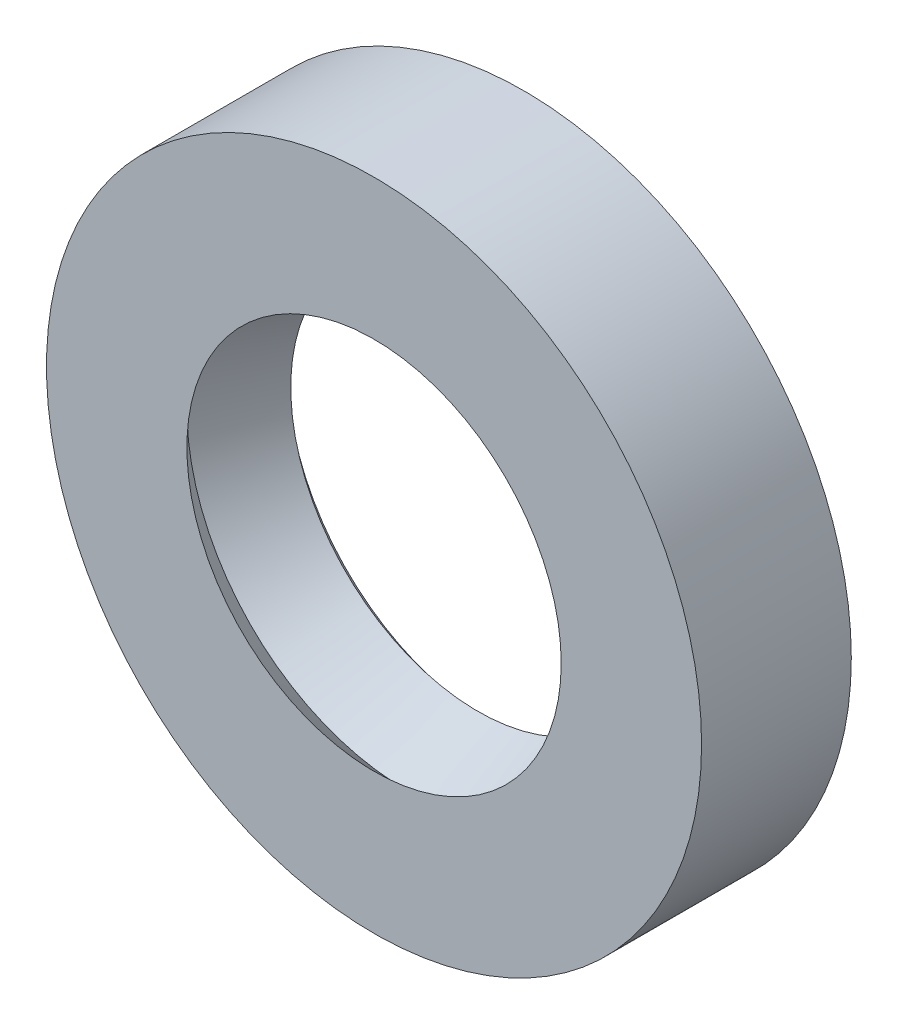
SolidWorks part; units mm, degrees
material "Silicon Rubber"
ref_plane "Front Plane" through (0, 0, 0) normal (0, 0, 1) x (1, 0, 0)
ref_plane "Top Plane" through (0, 0, 0) normal (0, 1, 0) x (1, 0, 0)
ref_plane "Right Plane" through (0, 0, 0) normal (1, 0, 0) x (0, 0, -1)
sketch "Sketch1" plane through (0, 0, 0) normal (1, 0, 0) x (0, 0, -1)
  line L0 (0, 17.5) -> (0, -17.5) construction
  line L1 (-20.6631, 0) -> (18.0254, 0) construction
  line L2 (0, 17.5) -> (-8, 17.5)
  line L3 (-8, 17.5) -> (-8, 0)
  line L4 (0, 15.75) -> (-6.25, 15.75)
  line L5 (-6.25, 15.75) -> (-6.25, 12.71)
  line L6 (-1.75, 12.1) -> (-2.45, 12.1)
  line L7 (-1.75, 12.1) -> (-1.75, 0)
  line L9 (-1.75, 10.875) -> (-2.45, 10)
  line L10 (-2.45, 10) -> (-6.25, 11.75)
  line L11 (-6.25, 11.75) -> (-8, 10)
  line L13 (-6.25, 12.71) -> (-3.85, 12.1)
  line L14 (0, 17.5) -> (0, 0)
  line L15 (-8, 0) -> (0, 0)
  arc A1 (-3.85, 12.1) -> (-2.45, 12.1) centre (-3.15, 12.1) cw
  point P4 (0, 0)
  dimension "D9" = 0.7
  dimension "D11" = 0.7
  dimension "D2" = 8
  dimension "D3" = 6.25
  dimension "D4" = 15.75
  dimension "D5" = 12.71
  dimension "D6" = 1.75
  dimension "D7" = 12.1
  dimension "D8" = 10.875
  dimension "D10" = 1.4
  dimension "D12" = 10
  dimension "D13" = 11.75
  dimension "D14" = 10
  dimension "D15" = 1.75
  dimension "D16" = 17.5
revolve "Revolve3" add sketch "Sketch1" angle 360 about L1
